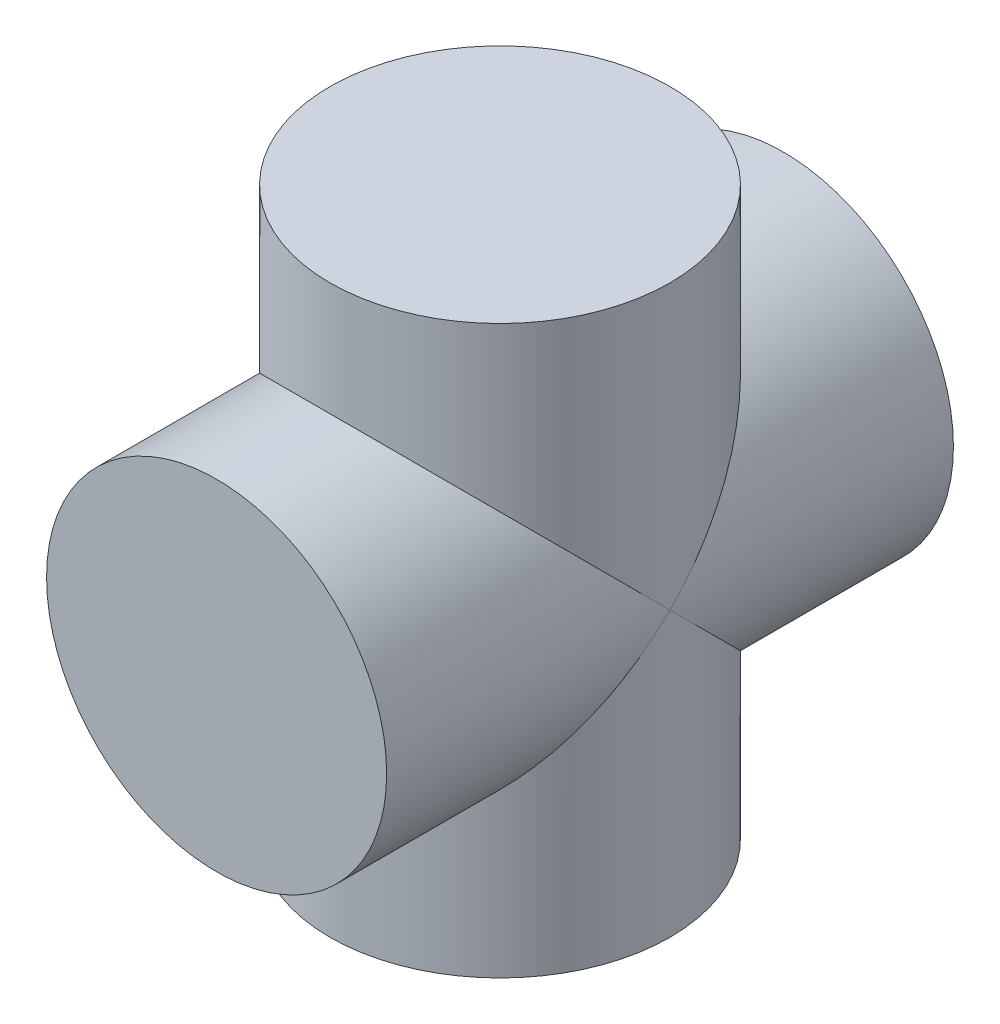
SolidWorks part; units mm, degrees
ref_plane "前视基准面" through (0, 0, 0) normal (0, 0, 1) x (1, 0, 0)
ref_plane "上视基准面" through (0, 0, 0) normal (0, 1, 0) x (1, 0, 0)
ref_plane "右视基准面" through (0, 0, 0) normal (1, 0, 0) x (0, 0, -1)
sketch "草图1" plane through (0, 0, 0) normal (0, 0, 1) x (1, 0, 0)
  circle A0 centre (0, 0) radius 30
  dimension "D1" = 60
extrude "凸台-拉伸1" add sketch "草图1" along normal mid plane 100
sketch "草图2" plane through (0, 0, 0) normal (0, 1, 0) x (1, 0, 0)
  circle A0 centre (0, 0) radius 30
  dimension "D1" = 60
extrude "凸台-拉伸2" add sketch "草图2" along normal mid plane 100
